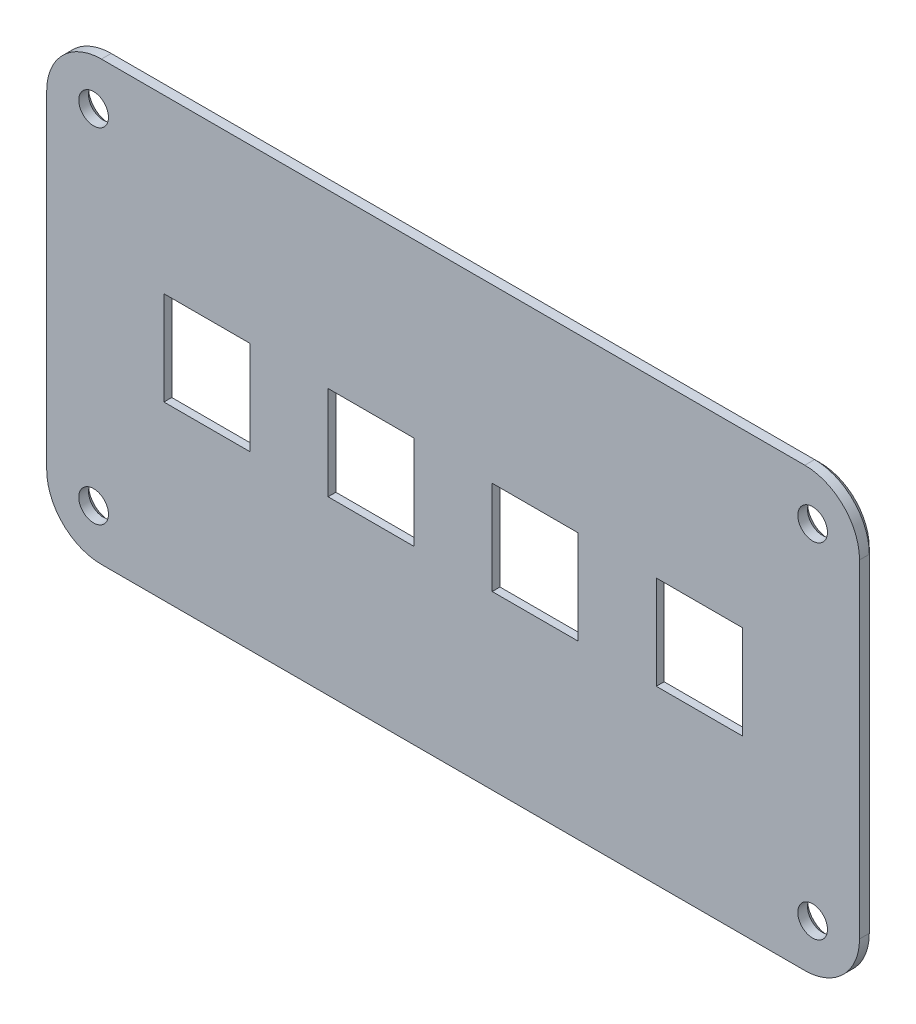
SolidWorks part; units mm, degrees
ref_plane "Front Plane" through (0, 0, 0) normal (0, 0, 1) x (1, 0, 0)
ref_plane "Top Plane" through (0, 0, 0) normal (0, 1, 0) x (1, 0, 0)
ref_plane "Right Plane" through (0, 0, 0) normal (1, 0, 0) x (0, 0, -1)
sketch "Sketch1" plane through (0, 0, 0) normal (0, 0, 1) x (1, 0, 0)
  line L2 (-42, -26) -> (42, -26) construction
  line L5 (50, -18) -> (50, 18) construction
  line L8 (42, 26) -> (-42, 26) construction
  line L11 (-50, 18) -> (-50, -18) construction
  line L12 (-52, 21) -> (-52, -21) construction
  line L13 (-45, -28) -> (45, -28) construction
  line L14 (52, -21) -> (52, 21) construction
  line L15 (45, 28) -> (-45, 28) construction
  line L16 (-50, -18) -> (-45, -18)
  line L17 (-42, -21) -> (-42, -26)
  line L18 (-42, -26) -> (42, -26)
  line L19 (42, -21) -> (42, -26)
  line L20 (50, -18) -> (45, -18)
  line L21 (50, -18) -> (50, 18)
  line L22 (50, 18) -> (45, 18)
  line L23 (42, 21) -> (42, 26)
  line L24 (42, 26) -> (-42, 26)
  line L25 (-42, 21) -> (-42, 26)
  line L26 (-42, -21) -> (-42, -17)
  line L27 (-42, -8) -> (27, -8)
  line L28 (-42, -21) -> (-42, -17)
  line L29 (-42, -17) -> (-42, -8)
  line L30 (27, -26) -> (45, -26)
  line L31 (50, -21) -> (50, -0.25)
  line L32 (50, -0.25) -> (43.9, -0.25)
  line L33 (43.9, -0.25) -> (43.9, 19.75)
  line L34 (43.9, 19.75) -> (50, 19.75)
  line L35 (50, 19.75) -> (50, 21)
  line L36 (45, 26) -> (38.9, 26)
  line L37 (38.9, 26) -> (38.9, 25)
  line L38 (38.9, 25) -> (18.9, 25)
  line L39 (18.9, 25) -> (18.9, 26)
  line L40 (18.9, 26) -> (-22.5, 26)
  line L41 (-22.5, 26) -> (-22.5, 25)
  line L42 (-22.5, 25) -> (-42.5, 25)
  line L43 (-42.5, 25) -> (-42.5, 26)
  line L44 (-42.5, 26) -> (-45, 26)
  line L45 (-50, 21) -> (-50, 17.22)
  line L46 (-50, 17.22) -> (-47.5, 14.72)
  line L47 (-47.5, 14.72) -> (-47.5, -0.28)
  line L48 (-47.5, -0.28) -> (-50, -2.78)
  line L49 (-50, -2.78) -> (-50, -18)
  line L50 (-42, -17) -> (-42, -8)
  line L51 (27, -8) -> (27, -17)
  line L66 (18.9, 26) -> (-22.5, 26)
  line L78 (-50, 18) -> (-45, 18)
  line L79 (-50, 18) -> (-50, -18)
  line L80 (-52, 21) -> (-52, -21)
  line L81 (-45, -28) -> (45, -28)
  line L82 (52, -21) -> (52, 21)
  line L83 (45, 28) -> (-45, 28)
  line L84 (-52, 0) -> (-37.861, 0) construction
  line L139 (-50, -18) -> (-45, -18)
  line L140 (-50, -18) -> (-45, -18)
  line L141 (27, -8) -> (27, -17)
  line L142 (27, -17) -> (27, -26)
  line L169 (27, -17) -> (27, -26)
  arc A4 (45, -26) -> (50, -21) centre (45, -21) ccw
  arc A5 (50, 21) -> (45, 26) centre (45, 21) ccw
  arc A6 (-45, 26) -> (-50, 21) centre (-45, 21) ccw
  arc A7 (-42, -21) -> (-45, -18) centre (-45, -21) ccw
  arc A15 (-52, -21) -> (-45, -28) centre (-45, -21) ccw construction
  arc A16 (45, -28) -> (52, -21) centre (45, -21) ccw construction
  arc A17 (52, 21) -> (45, 28) centre (45, 21) ccw construction
  arc A18 (-45, 28) -> (-52, 21) centre (-45, 21) ccw construction
  circle A19 centre (46, -22) radius 1.5
  circle A20 centre (46, 22) radius 1.5
  circle A21 centre (-46, 22) radius 1.5
  arc A22 (-42, -21) -> (-45, -18) centre (-49.6725, -25.6725) ccw
  arc A23 (45, -18) -> (42, -21) centre (45, -21) ccw
  arc A24 (42, 21) -> (45, 18) centre (45, 21) ccw
  arc A25 (-45, 18) -> (-42, 21) centre (-45, 21) ccw
  arc A26 (-52, -21) -> (-45, -28) centre (-45, -21) ccw
  arc A27 (45, -28) -> (52, -21) centre (45, -21) ccw
  arc A28 (52, 21) -> (45, 28) centre (45, 21) ccw
  arc A29 (-45, 28) -> (-52, 21) centre (-45, 21) ccw
  circle A30 centre (-46, -22) radius 1.5
  circle A31 centre (-46, 22) radius 1.9
  circle A32 centre (46, 22) radius 1.9
  circle A33 centre (46, -22) radius 1.9
  circle A34 centre (-46, -22) radius 1.9
  arc A43 (-42, -21) -> (-45, -18) centre (-45, -21) ccw
  dimension "D10" = 3.8
  dimension "D11" = 3
  dimension "D4" = 104
  dimension "D5" = 56
  dimension "D6" = 6
  dimension "D7" = 6
  dimension "D8" = 10
  dimension "D9" = 10
  dimension "D1" = 0
  dimension "D2" = 0.4
  dimension "D3" = 0.4
extrude "Boss-Extrude1" add sketch "Sketch1" along normal blind 2 contours A29 L80 A26 L81 A27 L82 A28 L83 | A31 | A34 | A33 | A32
sketch "Sketch2" plane through (0, 0, 0) normal (0, 0, -1) x (-1, 0, 0)
  line L0 (-52, 0) -> (52, 0) construction
  line L1 (-52, -21) -> (-52, 21) construction
  line L2 (52, 21) -> (52, -21) construction
  line L3 (0, 0) -> (0, -28) construction
  line L4 (-37, -6) -> (-26, -6)
  line L5 (-37, -6) -> (-37, 6)
  line L6 (-37, 6) -> (-26, 6)
  line L7 (-26, -6) -> (-26, 6)
  line L8 (-37, -6) -> (-26, 6) construction
  line L9 (-37, 6) -> (-26, -6) construction
  line L10 (-16, -6) -> (-5, -6)
  line L11 (-16, -6) -> (-16, 6)
  line L12 (-16, 6) -> (-5, 6)
  line L13 (-5, -6) -> (-5, 6)
  line L14 (-16, -6) -> (-5, 6) construction
  line L15 (-16, 6) -> (-5, -6) construction
  line L16 (5, -6) -> (16, -6)
  line L17 (5, -6) -> (5, 6)
  line L18 (5, 6) -> (16, 6)
  line L19 (16, -6) -> (16, 6)
  line L20 (5, -6) -> (16, 6) construction
  line L21 (5, 6) -> (16, -6) construction
  line L22 (26, -6) -> (37, -6)
  line L23 (26, -6) -> (26, 6)
  line L24 (26, 6) -> (37, 6)
  line L25 (37, -6) -> (37, 6)
  line L26 (26, -6) -> (37, 6) construction
  line L27 (26, 6) -> (37, -6) construction
  line L28 (45, -28) -> (-45, -28) construction
  point P6 (-31.5, 0)
  point P11 (-10.5, 0)
  point P16 (10.5, 0)
  point P21 (31.5, 0)
  dimension "D1" = 11
  dimension "D2" = 12
  dimension "D3" = 11
  dimension "D4" = 11
  dimension "D5" = 11
  dimension "D6" = 12
  dimension "D7" = 12
  dimension "D8" = 12
  dimension "D9" = 5
  dimension "D10" = 5
  dimension "D11" = 10
  dimension "D12" = 10
extrude "Cut-Extrude1" cut sketch "Sketch2" against normal up to next
chamfer "Chamfer1" distance 1 angle 45 16 edges at (-26, 0, 0) (-31.5, -6, 0) (-37, 0, 0) (-31.5, 6, 0) (-5, 0, 0) (-10.5, -6, 0) (-16, 0, 0) (-10.5, 6, 0) (16, 0, 0) (10.5, -6, 0) (5, 0, 0) (10.5, 6, 0) (37, 0, 0) (31.5, -6, 0) (26, 0, 0) (31.5, 6, 0)
sketch "Sketch3" plane through (0, 0, 0) normal (0, 0, -1) x (-1, 0, 0)
  line L0 (25, 7) -> (38, 7) construction
  line L1 (4, 7) -> (17, 7) construction
  line L2 (-17, 7) -> (-4, 7) construction
  line L3 (-38, 7) -> (-25, 7) construction
  line L4 (25, 7) -> (38, 7) construction
  line L5 (4, 7) -> (17, 7) construction
  line L6 (-17, 7) -> (-4, 7) construction
  line L7 (-38, 7) -> (-25, 7) construction
  line L8 (-38, 11) -> (-25, 11) construction
  line L9 (-17, 11) -> (-4, 11) construction
  line L10 (4, 11) -> (17, 11) construction
  line L11 (25, 11) -> (38, 11) construction
  text T0 "<b>A</b>" font "Montserrat Medium" height 10
  text T1 "<b>B</b>" font "Montserrat Medium" height 10
  text T2 "<b>C</b>" font "Montserrat Medium" height 10
  text T3 "<b>D</b>" font "Montserrat Medium" height 10
  dimension "D1" = 4
extrude "Boss-Extrude2" add sketch "Sketch3" along normal blind 1
chamfer "Chamfer2" distance 0.75 angle 45 12 edges at (-47.9, -22, 0) (47.9, -22, 0) (-44.1, 22, 0) (47.9, 22, 0) (-49.9497, 25.9497, 0) (-52, 0, 0) (-49.9497, -25.9497, 0) (0, -28, 0) (49.9497, -25.9497, 0) (52, 0, 0) (49.9497, 25.9497, 0) (0, 28, 0)
